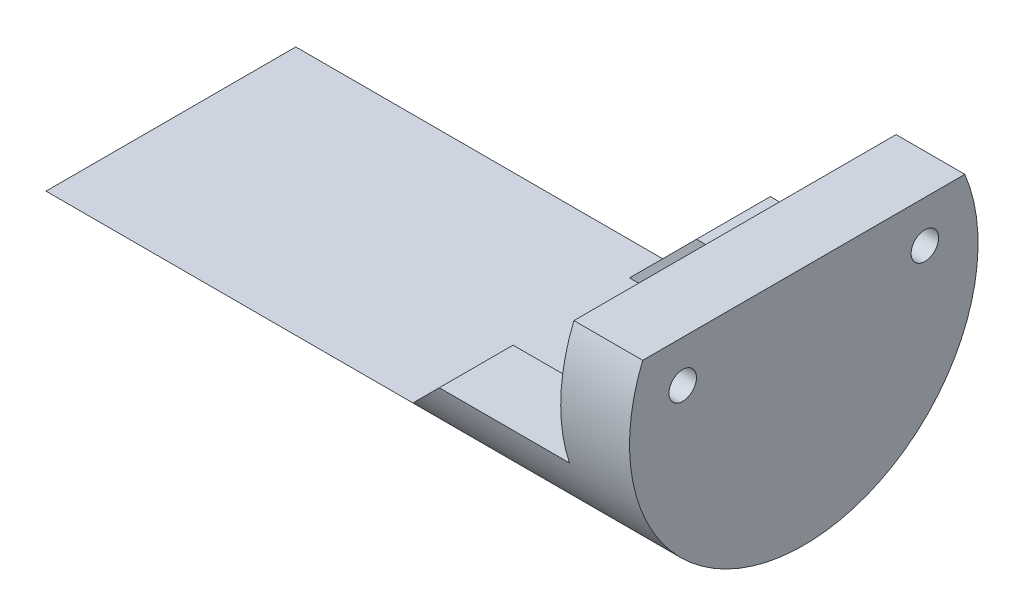
SolidWorks part; units mm, degrees
ref_plane "前视基准面" through (0, 0, 0) normal (0, 0, 1) x (1, 0, 0)
ref_plane "上视基准面" through (0, 0, 0) normal (0, 1, 0) x (1, 0, 0)
ref_plane "右视基准面" through (0, 0, 0) normal (1, 0, 0) x (0, 0, -1)
sketch "草图1" plane through (0, 0, 0) normal (1, 0, 0) x (0, 0, -1)
  circle A0 centre (0, 0) radius 19
  dimension "D1" = 38
extrude "凸台-拉伸1" add sketch "草图1" along normal blind 69
sketch "草图3" plane through (0, 0, 0) normal (0, 0, 1) x (1, 0, 0)
  line L0 (69, 7.25) -> (61.5, 7.25)
  line L1 (69, -19) -> (69, 19) construction
  line L2 (61.5, 7.25) -> (69, 7.25) construction
  line L3 (61.5, 7.25) -> (61.5, -5.9447)
  line L4 (61.5, -5.9447) -> (47.3053, -5.9447)
  line L5 (47.3053, -5.9447) -> (40, -13.25)
  line L6 (40, -13.25) -> (0, -13.25)
  line L7 (0, 19) -> (0, -19) construction
  line L8 (0, -13.25) -> (0, 41.3606)
  line L9 (0, 41.3606) -> (69, 41.3606)
  line L10 (69, 41.3606) -> (69, 7.25)
extrude "切除-拉伸1" cut sketch "草图3" against normal through all both and the other way through all
sketch "草图4" plane through (61.5, 0, 0) normal (-1, 0, 0) x (0, 0, 1)
  line L0 (0, 2.3601) -> (0, -2.2945) construction
  line L1 (10, 0.75) -> (10, -13.25)
  line L3 (-10, -13.25) -> (-10, 0.75)
  line L5 (10, -13.25) -> (-10, -13.25)
  line L7 (-10, 0.75) -> (10, 0.75)
  line L9 (-13.6175, -13.25) -> (13.6175, -13.25) construction
  dimension "D1" = 20
extrude "切除-拉伸2" cut sketch "草图4" along normal through all
sketch "草图5" plane through (61.5, 0, 0) normal (-1, 0, 0) x (0, 0, 1)
  line L0 (-10, -13.25) -> (10, -13.25) construction
  line L1 (-10, -13.25) -> (10, -13.25)
  line L2 (-10, -13.25) -> (-10, 5.7814)
  line L3 (-10, 5.7814) -> (10, 5.7814)
  line L4 (10, -13.25) -> (10, 5.7814)
  line L5 (-10, -5.9447) -> (-10, -13.25) construction
  line L6 (10, -13.25) -> (10, -5.9447) construction
extrude "切除-拉伸3" cut sketch "草图5" against normal blind 6 contours L4 L3 L2 L1
sketch "草图6" plane through (69, 0, 0) normal (1, 0, 0) x (0, 0, -1)
  circle A0 centre (13.2, 2.7) radius 1.15 construction
  circle A1 centre (-13.2, 2.7) radius 1.15 construction
  circle A2 centre (13.2, 2.7) radius 1.15 construction
  circle A3 centre (-13.2, 2.7) radius 1.15 construction
  circle A4 centre (-13.2, 2.7) radius 0.75
  circle A5 centre (13.2, 2.7) radius 0.75
  dimension "D1" = 1.5
extrude "切除-拉伸4" cut sketch "草图6" against normal through all
sketch "草图7" plane through (69, 0, 0) normal (1, 0, 0) x (0, 0, -1)
  circle A0 centre (-13.2, 2.7) radius 1.5
  circle A1 centre (13.2, 2.7) radius 1.5
  dimension "D1" = 3
  dimension "D2" = 3
extrude "切除-拉伸5" cut sketch "草图7" against normal offset from surface (6.5 mm away) 1 up to face at (61.5, 2.7, 12.45)
